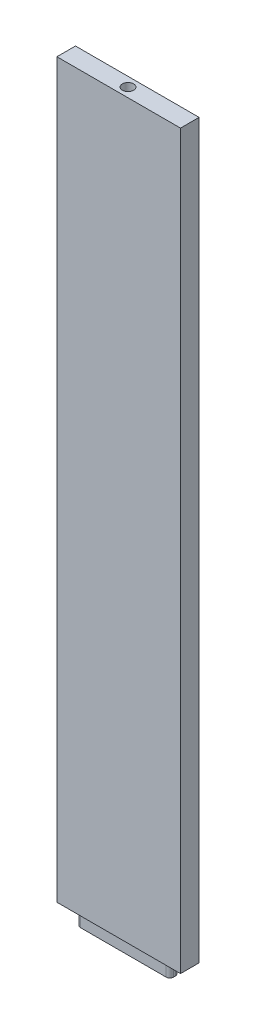
SolidWorks part; units mm, degrees
ref_plane "Alzado" through (0, 0, 0) normal (0, 0, 1) x (1, 0, 0)
ref_plane "Planta" through (0, 0, 0) normal (0, 1, 0) x (1, 0, 0)
ref_plane "Vista lateral" through (0, 0, 0) normal (1, 0, 0) x (0, 0, -1)
sketch "Croquis1" plane through (0, 0, 0) normal (0, 0, 1) x (1, 0, 0)
  line L1 (16.625, 98.5) -> (-16.625, 98.5)
  line L2 (16.625, 98.5) -> (16.625, -98.5)
  line L3 (16.625, -98.5) -> (-16.625, -98.5)
  line L4 (-16.625, 98.5) -> (-16.625, -98.5)
  line L5 (16.625, 98.5) -> (-16.625, -98.5) construction
  line L6 (16.625, -98.5) -> (-16.625, 98.5) construction
  point P0 (0, 0)
  dimension "D1" = 197
  dimension "D2" = 33.25
extrude "Saliente-Extruir1" add sketch "Croquis1" along normal blind 5
sketch "Croquis2" plane through (0, 98.5, 0) normal (0, 1, 0) x (1, 0, 0)
  line L0 (-16.625, -2.5) -> (16.625, -2.5) construction
  line L1 (-16.625, -5) -> (-16.625, 0) construction
  line L2 (16.625, -5) -> (16.625, 0) construction
  circle A0 centre (0, -2.5) radius 1.5
  dimension "D1" = 3
extrude "Cortar-Extruir1" cut sketch "Croquis2" against normal blind 15
sketch "Croquis3" plane through (0, -98.5, 0) normal (0, -1, 0) x (1, 0, 0)
  line L0 (-16.625, 2.5) -> (16.625, 2.5) construction
  line L1 (-16.625, 5) -> (-16.625, 0) construction
  line L2 (16.625, 5) -> (16.625, 0) construction
  line L4 (12.5, 3.75) -> (-12.5, 3.75)
  line L5 (12.5, 3.75) -> (12.5, 1.25)
  line L6 (12.5, 1.25) -> (-12.5, 1.25)
  line L7 (-12.5, 3.75) -> (-12.5, 1.25)
  line L8 (12.5, 3.75) -> (-12.5, 1.25) construction
  line L9 (12.5, 1.25) -> (-12.5, 3.75) construction
  point P6 (0, 2.5)
  dimension "D1" = 25
  dimension "D2" = 2.5
extrude "Saliente-Extruir2" add sketch "Croquis3" along normal blind 4
fillet "Redondeo2" radius 1 4 edges at (12.5, -100.5, 1.25) (12.5, -100.5, 3.75) (-12.5, -100.5, 3.75) (-12.5, -100.5, 1.25)
